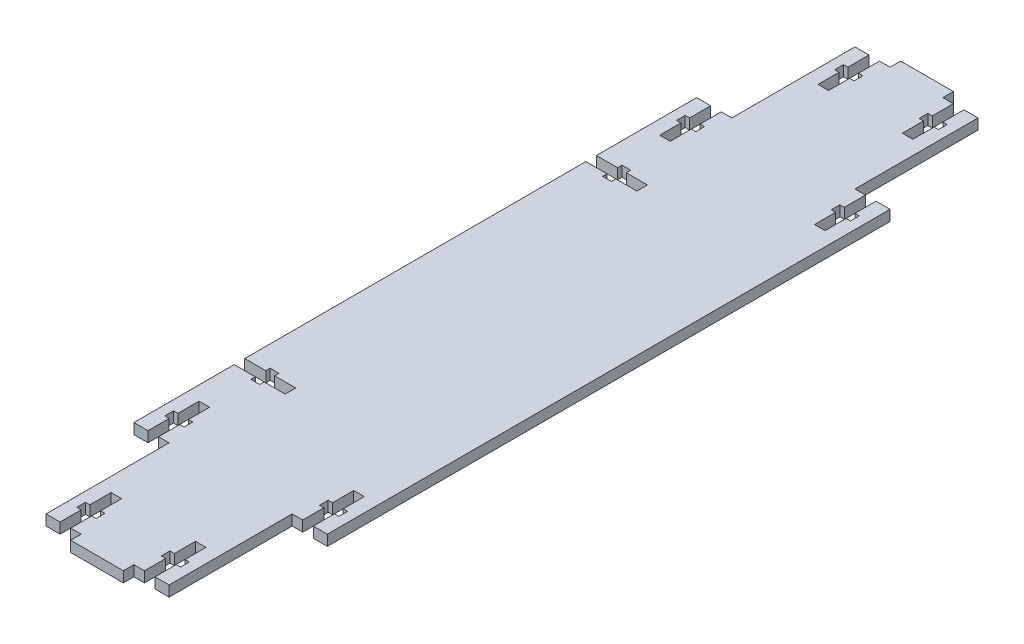
SolidWorks part; units mm, degrees
ref_plane "Спереди" through (0, 0, 0) normal (0, 0, 1) x (1, 0, 0)
ref_plane "Сверху" through (0, 0, 0) normal (0, 1, 0) x (1, 0, 0)
ref_plane "Справа" through (0, 0, 0) normal (1, 0, 0) x (0, 0, -1)
sketch "Эскиз1" plane through (0, 0, 0) normal (0, 1, 0) x (1, 0, 0)
  line L1 (-27.5, -80) -> (27.5, -80)
  line L2 (-27.5, -80) -> (-27.5, 80)
  line L3 (-27.5, 80) -> (27.5, 80)
  line L4 (27.5, -80) -> (27.5, 80)
  line L5 (-27.5, -80) -> (27.5, 80) construction
  line L6 (-27.5, 80) -> (27.5, -80) construction
  point P0 (0, 0)
  dimension "D1" = 55
  dimension "D2" = 160
extrude "Бобышка-Вытянуть1" add sketch "Эскиз1" along normal blind 3
sketch "Эскиз2" plane through (0, 0, -80) normal (0, 0, -1) x (-1, 0, 0)
  line L0 (-27.5, 0) -> (27.5, 0) construction
  line L1 (-17.5, 0) -> (17.5, 0)
  line L2 (-17.5, 0) -> (-17.5, 3)
  line L3 (-17.5, 3) -> (17.5, 3)
  line L4 (17.5, 0) -> (17.5, 3)
  line L5 (-27.5, 3) -> (27.5, 3) construction
  point P8 (0, 3)
  dimension "D1" = 35
  dimension "D2" = 27.5
extrude "Бобышка-Вытянуть2" add sketch "Эскиз2" along normal blind 35 and the other way blind 195
sketch "Эскиз3" plane through (0, 0, -115) normal (0, 0, -1) x (-1, 0, 0)
  line L0 (-17.5, 0) -> (17.5, 0) construction
  line L1 (-7.5, 0) -> (7.5, 0)
  line L2 (-7.5, 0) -> (-7.5, 3)
  line L3 (-7.5, 3) -> (7.5, 3)
  line L4 (7.5, 0) -> (7.5, 3)
  line L5 (17.5, 3) -> (-17.5, 3) construction
  point P8 (0, 0)
  dimension "D1" = 15
  dimension "D2" = 27.5
extrude "Бобышка-Вытянуть3" add sketch "Эскиз3" along normal blind 3 and the other way blind 233
sketch "Эскиз4" plane through (0, 3, 0) normal (0, 1, 0) x (1, 0, 0)
  line L0 (-23.5, 80) -> (-23.5, 74)
  line L1 (-13.5, 115) -> (-13.5, 109)
  line L2 (-23.5, 74) -> (-24.75, 74)
  line L3 (-24.75, 74) -> (-24.75, 71.5)
  line L4 (-24.75, 71.5) -> (-23.5, 71.5)
  line L5 (-23.5, 71.5) -> (-23.5, 65.5)
  line L6 (-23.5, 65.5) -> (-20.5, 65.5)
  line L7 (-20.5, 65.5) -> (-20.5, 71.5)
  line L8 (-20.5, 71.5) -> (-19.25, 71.5)
  line L9 (-19.25, 71.5) -> (-19.25, 74)
  line L10 (-19.25, 74) -> (-20.5, 74)
  line L11 (-20.5, 74) -> (-20.5, 80)
  line L12 (-13.5, 109) -> (-14.75, 109)
  line L13 (-20.5, 80) -> (-23.5, 80)
  line L14 (-14.75, 109) -> (-14.75, 106.5)
  line L15 (-14.75, 106.5) -> (-13.5, 106.5)
  line L16 (-13.5, 106.5) -> (-13.5, 100.5)
  line L17 (-13.5, 100.5) -> (-10.5, 100.5)
  line L18 (-10.5, 100.5) -> (-10.5, 106.5)
  line L19 (-10.5, 106.5) -> (-9.25, 106.5)
  line L20 (-9.25, 106.5) -> (-9.25, 109)
  line L21 (-9.25, 109) -> (-10.5, 109)
  line L22 (-10.5, 109) -> (-10.5, 115)
  line L23 (-10.5, 115) -> (-13.5, 115)
  line L24 (-17.5, 80) -> (-27.5, 80) construction
  line L25 (-17.5, 115) -> (-7.5, 115) construction
  line L26 (0, 118) -> (0, 75.6534) construction
  line L27 (-7.5, 118) -> (7.5, 118) construction
  line L28 (-27.5, 0) -> (22.9967, 0) construction
  line L29 (-27.5, 80) -> (-27.5, -80) construction
  line L30 (10.5, 115) -> (13.5, 115)
  line L31 (10.5, 109) -> (10.5, 115)
  line L32 (9.25, 109) -> (10.5, 109)
  line L33 (9.25, 106.5) -> (9.25, 109)
  line L34 (10.5, 106.5) -> (9.25, 106.5)
  line L35 (10.5, 100.5) -> (10.5, 106.5)
  line L36 (13.5, 100.5) -> (10.5, 100.5)
  line L37 (13.5, 106.5) -> (13.5, 100.5)
  line L38 (14.75, 106.5) -> (13.5, 106.5)
  line L39 (14.75, 109) -> (14.75, 106.5)
  line L40 (20.5, 80) -> (23.5, 80)
  line L41 (13.5, 109) -> (14.75, 109)
  line L42 (20.5, 74) -> (20.5, 80)
  line L43 (19.25, 74) -> (20.5, 74)
  line L44 (19.25, 71.5) -> (19.25, 74)
  line L45 (20.5, 71.5) -> (19.25, 71.5)
  line L46 (20.5, 65.5) -> (20.5, 71.5)
  line L47 (23.5, 65.5) -> (20.5, 65.5)
  line L48 (23.5, 71.5) -> (23.5, 65.5)
  line L49 (24.75, 71.5) -> (23.5, 71.5)
  line L50 (24.75, 74) -> (24.75, 71.5)
  line L51 (23.5, 74) -> (24.75, 74)
  line L52 (13.5, 115) -> (13.5, 109)
  line L53 (23.5, 80) -> (23.5, 74)
  line L54 (-10.5, -115) -> (-13.5, -115)
  line L55 (-10.5, -109) -> (-10.5, -115)
  line L56 (-9.25, -109) -> (-10.5, -109)
  line L57 (-9.25, -106.5) -> (-9.25, -109)
  line L58 (-10.5, -106.5) -> (-9.25, -106.5)
  line L59 (-10.5, -100.5) -> (-10.5, -106.5)
  line L60 (-13.5, -100.5) -> (-10.5, -100.5)
  line L61 (-13.5, -106.5) -> (-13.5, -100.5)
  line L62 (-14.75, -106.5) -> (-13.5, -106.5)
  line L63 (-14.75, -109) -> (-14.75, -106.5)
  line L64 (-13.5, -109) -> (-14.75, -109)
  line L65 (-13.5, -115) -> (-13.5, -109)
  line L66 (13.5, -115) -> (13.5, -109)
  line L67 (13.5, -109) -> (14.75, -109)
  line L68 (14.75, -109) -> (14.75, -106.5)
  line L69 (14.75, -106.5) -> (13.5, -106.5)
  line L70 (13.5, -106.5) -> (13.5, -100.5)
  line L71 (13.5, -100.5) -> (10.5, -100.5)
  line L72 (10.5, -100.5) -> (10.5, -106.5)
  line L73 (10.5, -106.5) -> (9.25, -106.5)
  line L74 (9.25, -106.5) -> (9.25, -109)
  line L75 (9.25, -109) -> (10.5, -109)
  line L76 (10.5, -109) -> (10.5, -115)
  line L77 (10.5, -115) -> (13.5, -115)
  line L78 (-20.5, -80) -> (-23.5, -80)
  line L79 (-20.5, -74) -> (-20.5, -80)
  line L80 (-19.25, -74) -> (-20.5, -74)
  line L81 (-19.25, -71.5) -> (-19.25, -74)
  line L82 (-20.5, -71.5) -> (-19.25, -71.5)
  line L83 (-20.5, -65.5) -> (-20.5, -71.5)
  line L84 (-23.5, -65.5) -> (-20.5, -65.5)
  line L85 (-23.5, -71.5) -> (-23.5, -65.5)
  line L86 (-24.75, -71.5) -> (-23.5, -71.5)
  line L87 (-24.75, -74) -> (-24.75, -71.5)
  line L88 (-23.5, -74) -> (-24.75, -74)
  line L89 (-23.5, -80) -> (-23.5, -74)
  line L90 (23.5, -80) -> (23.5, -74)
  line L91 (23.5, -74) -> (24.75, -74)
  line L92 (24.75, -74) -> (24.75, -71.5)
  line L93 (24.75, -71.5) -> (23.5, -71.5)
  line L94 (23.5, -71.5) -> (23.5, -65.5)
  line L95 (23.5, -65.5) -> (20.5, -65.5)
  line L96 (20.5, -65.5) -> (20.5, -71.5)
  line L97 (20.5, -71.5) -> (19.25, -71.5)
  line L98 (19.25, -71.5) -> (19.25, -74)
  line L99 (19.25, -74) -> (20.5, -74)
  line L100 (20.5, -74) -> (20.5, -80)
  line L101 (20.5, -80) -> (23.5, -80)
  point P29 (-22, 80)
  point P112 (-12, 115)
  dimension "D1" = 3
  dimension "D2" = 5.5
  dimension "D3" = 6
  dimension "D4" = 2.5
  dimension "D5" = 3
  dimension "D6" = 5.5
  dimension "D7" = 6
  dimension "D8" = 2.5
  dimension "D9" = 4.5
  dimension "D10" = 4
  dimension "D11" = 4.5
extrude "Вырез-Вытянуть1" cut sketch "Эскиз4" against normal blind 3
sketch "Эскиз5" plane through (0, 3, 0) normal (0, 1, 0) x (1, 0, 0)
  line L0 (-27.5, 51.5) -> (-21.5, 51.5)
  line L1 (-21.5, 51.5) -> (-21.5, 52.75)
  line L2 (-21.5, 52.75) -> (-19, 52.75)
  line L3 (-19, 52.75) -> (-19, 51.5)
  line L4 (-19, 51.5) -> (-13, 51.5)
  line L5 (-13, 51.5) -> (-13, 48.5)
  line L6 (-13, 48.5) -> (-19, 48.5)
  line L7 (-19, 48.5) -> (-19, 47.25)
  line L8 (-19, 47.25) -> (-21.5, 47.25)
  line L9 (-21.5, 47.25) -> (-21.5, 48.5)
  line L10 (-21.5, 48.5) -> (-27.5, 48.5)
  line L11 (-27.5, 48.5) -> (-27.5, 51.5)
  line L12 (-27.5, 80) -> (-27.5, -80) construction
  line L13 (-27.5, 0) -> (-6.9327, 0) construction
  line L14 (-27.5, -48.5) -> (-27.5, -51.5)
  line L15 (-21.5, -48.5) -> (-27.5, -48.5)
  line L16 (-21.5, -47.25) -> (-21.5, -48.5)
  line L17 (-19, -47.25) -> (-21.5, -47.25)
  line L18 (-19, -48.5) -> (-19, -47.25)
  line L19 (-13, -48.5) -> (-19, -48.5)
  line L20 (-13, -51.5) -> (-13, -48.5)
  line L21 (-19, -51.5) -> (-13, -51.5)
  line L22 (-19, -52.75) -> (-19, -51.5)
  line L23 (-21.5, -52.75) -> (-19, -52.75)
  line L24 (-21.5, -51.5) -> (-21.5, -52.75)
  line L25 (-27.5, -51.5) -> (-21.5, -51.5)
  point P30 (-27.5, 50)
  dimension "D1" = 3
  dimension "D2" = 6
  dimension "D3" = 2.5
  dimension "D4" = 5.5
  dimension "D5" = 50
extrude "Вырез-Вытянуть2" cut sketch "Эскиз5" against normal blind 3
